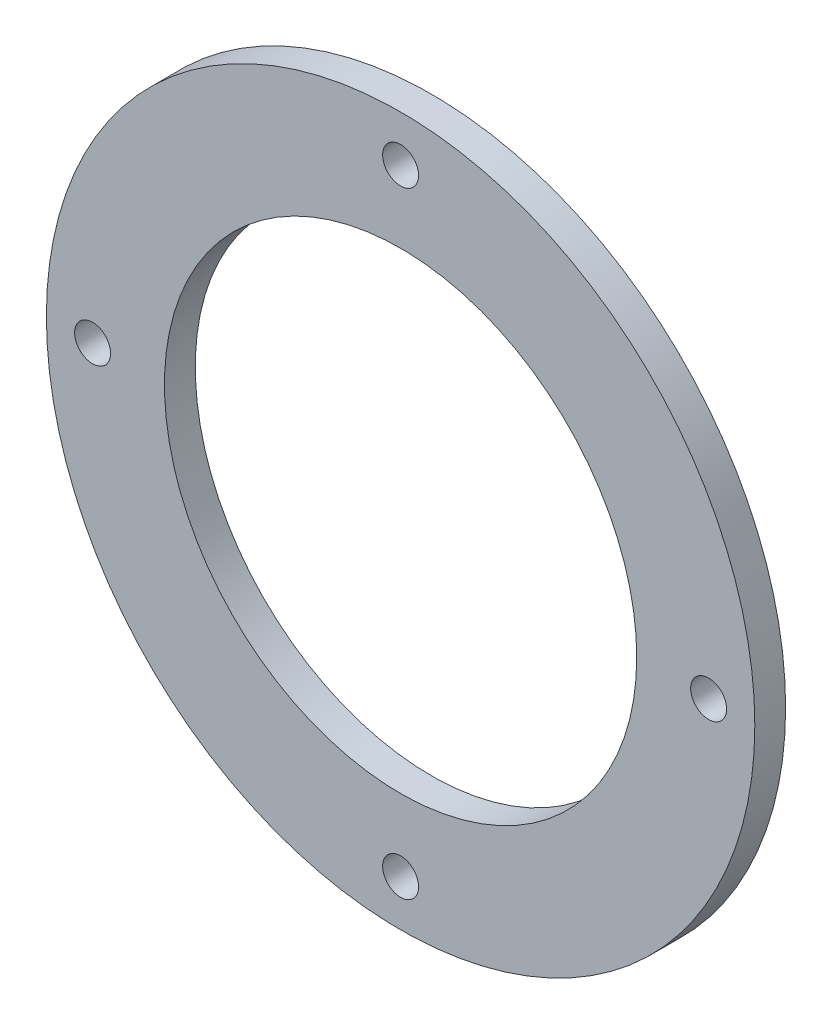
SolidWorks part; units mm, degrees
ref_plane "Front Plane" through (0, 0, 0) normal (0, 0, 1) x (1, 0, 0)
ref_plane "Top Plane" through (0, 0, 0) normal (0, 1, 0) x (1, 0, 0)
ref_plane "Right Plane" through (0, 0, 0) normal (1, 0, 0) x (0, 0, -1)
sketch "Sketch1" plane through (0, 0, 0) normal (0, 0, 1) x (1, 0, 0)
  circle A0 centre (0, 0) radius 23
  circle A1 centre (0, 0) radius 34.5
  circle A2 centre (0, 30) radius 1.75
  circle A3 centre (30, 0) radius 1.75
  circle A4 centre (0, -30) radius 1.75
  circle A5 centre (-30, 0) radius 1.75
  circle A6 centre (0, 0) radius 30 construction
  point P7 (0, 0)
  point P8 (30, 0)
  point P15 (0, 0)
  dimension "D1" = 69
  dimension "D2" = 46
  dimension "D3" = 3.5
  dimension "D5" = 60
  dimension "D4" = 4
extrude "Boss-Extrude1" add sketch "Sketch1" along normal blind 3
